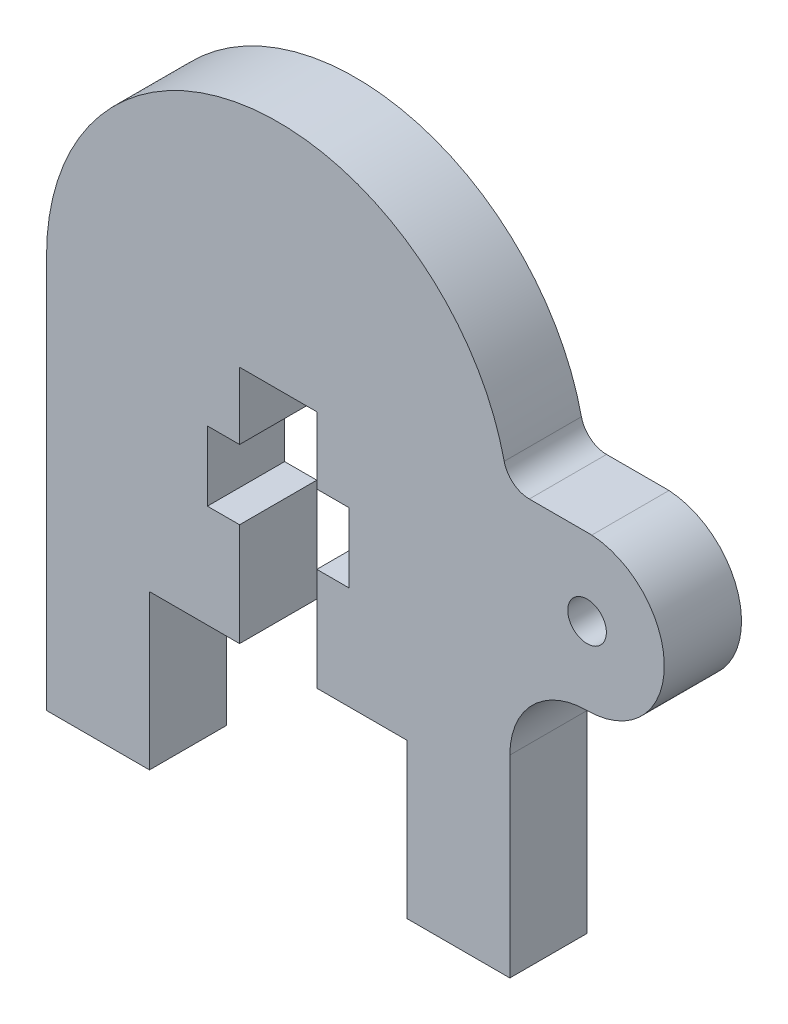
SolidWorks part; units mm, degrees
ref_plane "前视基准面" through (0, 0, 0) normal (0, 0, 1) x (1, 0, 0)
ref_plane "上视基准面" through (0, 0, 0) normal (0, 1, 0) x (1, 0, 0)
ref_plane "右视基准面" through (0, 0, 0) normal (1, 0, 0) x (0, 0, -1)
other "Configuration Table"
sketch "草图1" plane through (0, 0, 0) normal (0, 0, 1) x (1, 0, 0)
  line L0 (0, 0) -> (4, 0)
  line L1 (4, 0) -> (4, 6)
  line L2 (4, 6) -> (7.5, 6)
  line L3 (7.5, 6) -> (7.5, 10)
  line L4 (7.5, 10) -> (6.25, 10)
  line L5 (6.25, 10) -> (6.25, 12.7)
  line L6 (6.25, 12.7) -> (7.5, 12.7)
  line L7 (7.5, 12.7) -> (7.5, 15.3)
  line L8 (7.5, 15.3) -> (10.5, 15.3)
  line L9 (10.5, 15.3) -> (10.5, 12.7)
  line L10 (10.5, 12.7) -> (11.75, 12.7)
  line L11 (11.75, 12.7) -> (11.75, 10)
  line L12 (11.75, 10) -> (10.5, 10)
  line L13 (10.5, 10) -> (10.5, 6)
  line L14 (10.5, 6) -> (14, 6)
  line L15 (14, 6) -> (14, 0)
  line L16 (14, 0) -> (18, 0)
  line L17 (18, 0) -> (18, 7.5)
  line L18 (0, 0) -> (0, 15.3)
  line L19 (21.1833, 16.4944) -> (13.6539, 16.4944) construction
  line L20 (21.1833, 16.4944) -> (18.7563, 16.4944)
  arc A0 (18, 7.5) -> (21, 10.5) centre (21, 7.5) cw
  arc A1 (21, 10.5) -> (21.1833, 16.4944) centre (21, 13.5) ccw
  arc A2 (0, 15.3) -> (17.7806, 17.275) centre (9, 15.3) cw
  arc A3 (17.7806, 17.275) -> (18.7563, 16.4944) centre (18.7563, 17.4944) ccw
  circle A4 centre (21, 13.5) radius 0.75
  point P31 (17.9204, 16.4944)
  dimension "D13" = 3
  dimension "D14" = 3
  dimension "D15" = 3
  dimension "D16" = 1
  dimension "D17" = 1.5
  dimension "D1" = 4
  dimension "D2" = 6
  dimension "D3" = 3.5
  dimension "D4" = 4
  dimension "D5" = 1.25
  dimension "D6" = 2.7
  dimension "D7" = 2.6
  dimension "D8" = 3
  dimension "D9" = 1.25
  dimension "D10" = 3.5
  dimension "D11" = 4
  dimension "D12" = 7.5
extrude "凸台-拉伸1" add sketch "草图1" along normal blind 3
